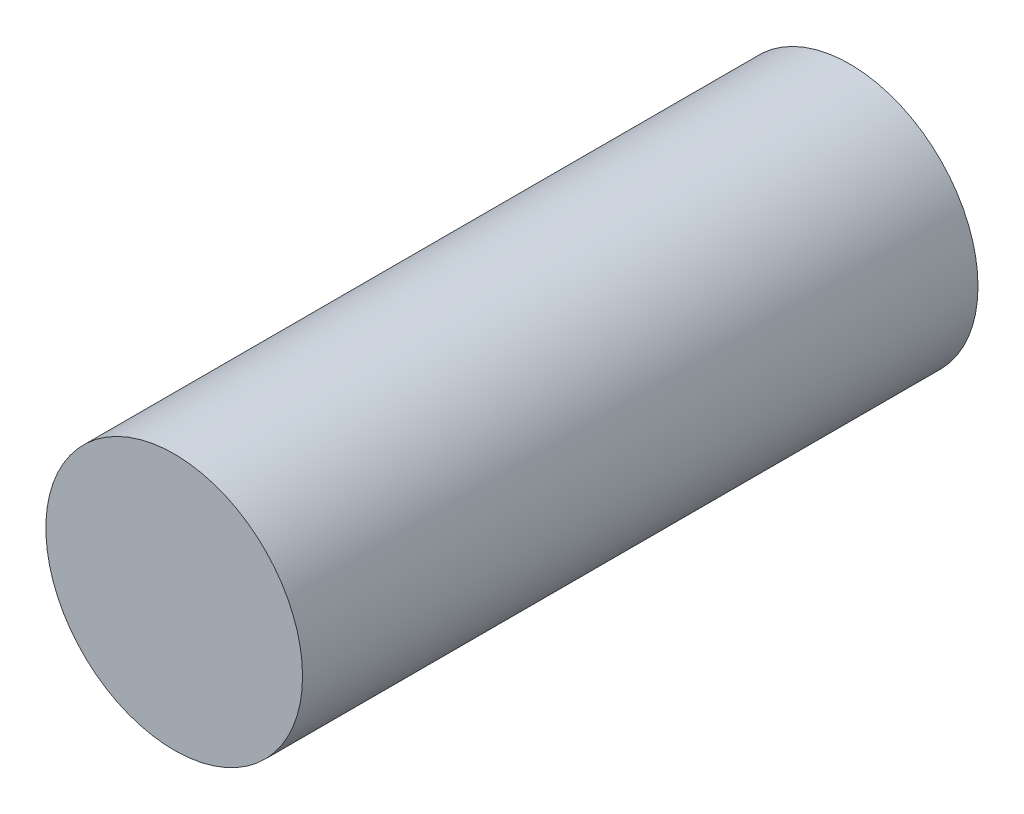
SolidWorks part; units mm, degrees
ref_plane "Front Plane" through (0, 0, 0) normal (0, 0, 1) x (1, 0, 0)
ref_plane "Top Plane" through (0, 0, 0) normal (0, 1, 0) x (1, 0, 0)
ref_plane "Right Plane" through (0, 0, 0) normal (1, 0, 0) x (0, 0, -1)
sketch "Sketch1" plane through (0, 0, 0) normal (0, 0, 1) x (1, 0, 0)
  circle A0 centre (0, 0) radius 4.75
  dimension "D1" = 9.5
extrude "Boss-Extrude1" add sketch "Sketch1" against normal blind 25
